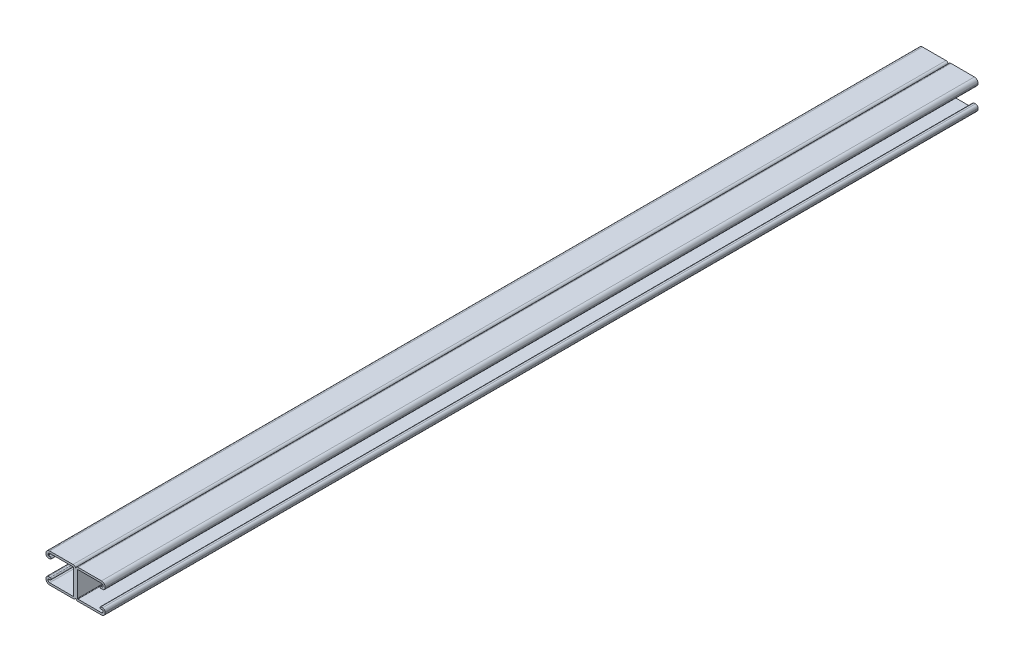
SolidWorks part; units mm, degrees
ref_plane "Front Plane" through (0, 0, 0) normal (0, 0, 1) x (1, 0, 0)
ref_plane "Top Plane" through (0, 0, 0) normal (0, 1, 0) x (1, 0, 0)
ref_plane "Right Plane" through (0, 0, 0) normal (1, 0, 0) x (0, 0, -1)
sketch "Sketch1" plane through (0, 0, 0) normal (0, 0, 1) x (1, 0, 0)
  line L0 (0, 0) -> (-41.275, 0) construction
  line L3 (-41.275, 20.6375) -> (0, 20.6375) construction
  line L4 (-41.275, 20.6375) -> (-41.275, -20.6375) construction
  line L5 (-41.275, -20.6375) -> (0, -20.6375) construction
  line L6 (0, 20.6375) -> (0, -20.6375) construction
  line L7 (-36.2267, 20.6375) -> (-3.4607, 20.6375)
  line L8 (0, 17.1767) -> (0, -17.1767)
  line L9 (-2.794, -17.1767) -> (-2.794, 17.1767)
  line L10 (-3.4608, 17.8435) -> (-36.2267, 17.8435)
  line L11 (-41.275, 15.5892) -> (-41.275, 14.5732)
  line L12 (-37.8142, 11.1125) -> (-35.5346, 11.1125)
  line L14 (-35.5346, 13.9065) -> (-37.8142, 13.9065)
  line L15 (-38.481, 14.5732) -> (-38.481, 15.5892)
  line L16 (-38.481, -14.5733) -> (-38.481, -15.5893)
  line L17 (-35.5346, -13.9065) -> (-37.8142, -13.9065)
  line L18 (-37.8142, -11.1125) -> (-35.5346, -11.1125)
  line L19 (-41.275, -15.5893) -> (-41.275, -14.5733)
  line L20 (-3.4607, -17.8435) -> (-36.2267, -17.8435)
  line L21 (-36.2267, -20.6375) -> (-3.4607, -20.6375)
  line L22 (-2.794, -20.6375) -> (-2.794, 20.6375) construction
  arc A1 (0, 17.1767) -> (-3.4607, 20.6375) centre (-3.4607, 17.1767) ccw
  arc A2 (-2.794, 17.1767) -> (-3.4608, 17.8435) centre (-3.4607, 17.1767) ccw
  arc A4 (-36.2267, 20.6375) -> (-41.275, 15.5892) centre (-36.2267, 15.5892) ccw
  arc A5 (-41.275, 14.5732) -> (-37.8142, 11.1125) centre (-37.8142, 14.5732) ccw
  arc A6 (-35.5346, 11.1125) -> (-35.5346, 13.9065) centre (-35.5346, 12.5095) ccw
  arc A7 (-37.8142, 13.9065) -> (-38.481, 14.5732) centre (-37.8142, 14.5732) cw
  arc A8 (-38.481, 15.5892) -> (-36.2267, 17.8435) centre (-36.2267, 15.5892) cw
  arc A9 (-38.481, -15.5893) -> (-36.2267, -17.8435) centre (-36.2267, -15.5893) ccw
  arc A10 (-37.8142, -13.9065) -> (-38.481, -14.5733) centre (-37.8142, -14.5733) ccw
  arc A11 (-35.5346, -11.1125) -> (-35.5346, -13.9065) centre (-35.5346, -12.5095) cw
  arc A12 (-41.275, -14.5733) -> (-37.8142, -11.1125) centre (-37.8142, -14.5733) cw
  arc A13 (-36.2267, -20.6375) -> (-41.275, -15.5893) centre (-36.2267, -15.5893) cw
  arc A14 (-2.794, -17.1767) -> (-3.4607, -17.8435) centre (-3.4607, -17.1767) cw
  arc A15 (0, -17.1767) -> (-3.4607, -20.6375) centre (-3.4607, -17.1767) cw
  point P24 (0, 20.6375)
  point P65 (-2.794, 0)
  dimension "D1" = 3.4608
  dimension "D2" = 5.0482
  dimension "D3" = 3.4608
  dimension "Ht." = 41.275
  dimension "Wd." = 41.275
  dimension "Thk." = 2.794
  dimension "D4" = 9.525
  dimension "D5" = 7.1374
extrude "Boss-Extrude1" add sketch "Sketch1" against normal blind 1219.2
sketch "Sketch3" plane through (0, 0, 0) normal (1, 0, 0) x (0, 0, -1)
  line L0 (0, 0) -> (1219.2, 0) construction
  point P2 (101.6, 0)
  point P3 (1117.6, 0)
  dimension "D1" = 101.6
  dimension "D2" = 101.6
  dimension "D3" = 1219.2
mirror "Mirror1" about plane through (0, 17.1767, -1219.2) normal (1, 0, 0) of bodies 114
combine bodies "Combine1" operation type add bodies to combine 117 114
equation "\"D3@Sketch3\" = \"Lg.@Boss-Extrude1\""
